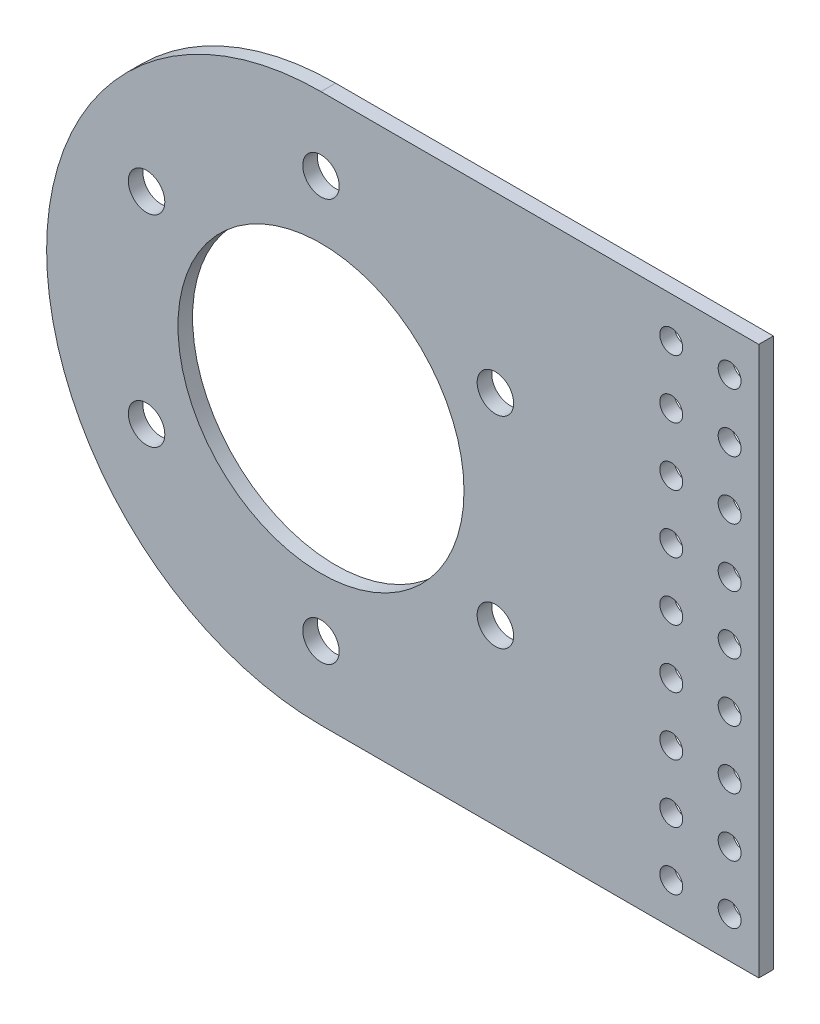
SolidWorks part; units mm, degrees
ref_plane "Front Plane" through (0, 0, 0) normal (1, 0, 0) x (0, 1, 0)
ref_plane "Top Plane" through (0, 0, 0) normal (0, 0, 1) x (0, 1, 0)
ref_plane "Right Plane" through (0, 0, 0) normal (0, 1, 0) x (-1, 0, 0)
sketch "Sketch1" plane through (0, 0, 0) normal (0, 0, 1) x (0, 1, 0)
  line L0 (-59.69, 0) -> (-59.69, -95.25)
  line L1 (-59.69, -95.25) -> (59.69, -95.25)
  line L2 (59.69, -95.25) -> (59.69, 0)
  circle A0 centre (0, 0) radius 25.4 construction
  circle A1 centre (0, 0) radius 27.94 construction
  circle A2 centre (0, 0) radius 43.815 construction
  circle A3 centre (-43.815, 0) radius 15.875 construction
  circle A4 centre (-21.9075, 37.9449) radius 15.875 construction
  circle A5 centre (21.9075, 37.9449) radius 15.875 construction
  circle A6 centre (43.815, 0) radius 15.875 construction
  circle A7 centre (21.9075, -37.9449) radius 15.875 construction
  circle A8 centre (-21.9075, -37.9449) radius 15.875 construction
  arc A9 (59.69, 0) -> (-59.69, 0) centre (0, 0) ccw
  circle A10 centre (0, 0) radius 31.115
  point P5 (-43.815, 0)
  point P8 (-21.9075, 37.9449)
  point P13 (21.9075, 37.9449)
  point P16 (43.815, 0)
  point P19 (21.9075, -37.9449)
  point P22 (-21.9075, -37.9449)
  point P25 (0, 0)
  dimension "D1" = 50.8
  dimension "D2" = 2.54
  dimension "D3" = 15.875
  dimension "D4" = 31.75
  dimension "D5" = 6
  dimension "D6" = 3.175
  dimension "D7" = 95.25
extrude "Boss-Extrude1" add sketch "Sketch1" along normal blind 3.175
sketch "Sketch2" plane through (0, 0, 3.175) normal (0, 0, 1) x (1, 0, 0)
  line L0 (95.25, -59.69) -> (95.25, 59.69) construction
  line L3 (88.9, -50.8) -> (88.9, -59.69) construction
  line L4 (0, -59.69) -> (95.25, -59.69) construction
  line L5 (88.9, 50.8) -> (88.9, 59.69) construction
  line L6 (95.25, 59.69) -> (0, 59.69) construction
  point P0 (88.9, -50.8)
  point P8 (76.2, -50.8)
  point P9 (76.2, -38.1)
  point P10 (76.2, -25.4)
  point P11 (76.2, -12.7)
  point P12 (76.2, 0)
  point P13 (76.2, 12.7)
  point P14 (76.2, 25.4)
  point P15 (76.2, 38.1)
  point P16 (76.2, 50.8)
  point P17 (88.9, -38.1)
  point P18 (88.9, -25.4)
  point P19 (88.9, -12.7)
  point P20 (88.9, 0)
  point P21 (88.9, 12.7)
  point P22 (88.9, 25.4)
  point P23 (88.9, 38.1)
  point P24 (88.9, 50.8)
  dimension "D1" = 6.35
  dimension "D2" = 2
  dimension "D5" = 12.7
  dimension "D6" = 12.7
  dimension "D4" = 9
hole_wizard "#9 (0.196) Diameter Hole1" positions "Sketch2" profile "Sketch3" hole size "#9" standard "ANSI Inch" end condition through all
sketch "Sketch3" plane through (88.9, -50.8, 3.175) normal (1, 0, 0) x (0, -1, 0)
  line L0 (0, 0) -> (0, 3.175)
  line L1 (0, 3.175) -> (2.4892, 3.175)
  line L2 (2.4892, 3.175) -> (2.4892, 0)
  line L5 (2.4892, 0) -> (0, 0)
  line L11 (0, -6.35) -> (0, 107.95) construction
  dimension "Thru Hole Dia." = 4.9784
  dimension "Thru Hole Depth" = 3.175
sketch "Sketch4" plane through (0, 0, 3.175) normal (0, 0, 1) x (1, 0, 0)
  point P0 (37.9449, 21.9075)
  point P2 (37.9449, -21.9075)
  point P4 (0, -43.815)
  point P6 (-37.9449, -21.9075)
  point P8 (-37.9449, 21.9075)
  point P10 (0, 43.815)
hole_wizard "5/16 (0.3125) Diameter Hole1" positions "Sketch4" profile "Sketch5" hole size "5/16" standard "ANSI Inch" end condition through all
sketch "Sketch5" plane through (37.9449, 21.9075, 3.175) normal (1, 0, 0) x (0, -1, 0)
  line L0 (0, 0) -> (0, 3.175)
  line L1 (0, 3.175) -> (3.9687, 3.175)
  line L2 (3.9687, 3.175) -> (3.9688, 0)
  line L5 (3.9688, 0) -> (0, 0)
  line L11 (0, -6.35) -> (0, 107.95) construction
  dimension "Thru Hole Dia." = 7.9375
  dimension "Thru Hole Depth" = 3.175
